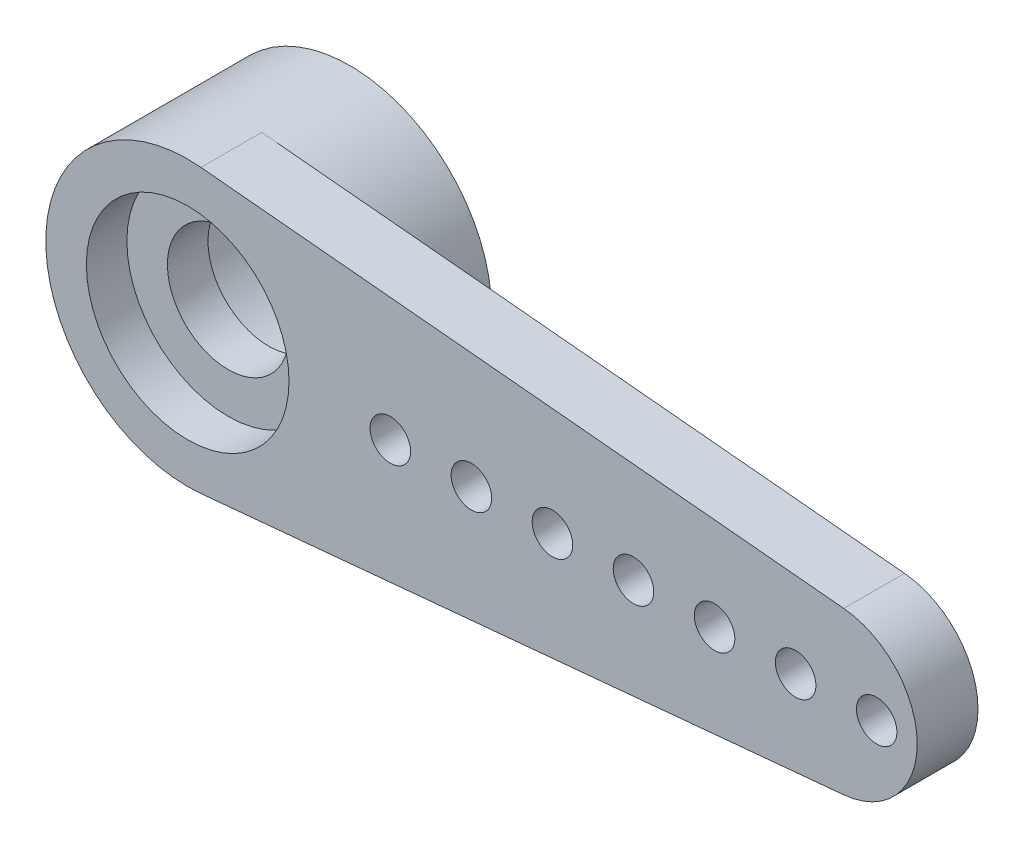
SolidWorks part; units mm, degrees
ref_plane "前视基准面" through (0, 0, 0) normal (0, 0, 1) x (1, 0, 0)
ref_plane "上视基准面" through (0, 0, 0) normal (0, 1, 0) x (1, 0, 0)
ref_plane "右视基准面" through (0, 0, 0) normal (1, 0, 0) x (0, 0, -1)
sketch "草图1" plane through (0, 0, 0) normal (0, 0, 1) x (1, 0, 0)
  circle A0 centre (0, 0) radius 3.5
  dimension "D1" = 7
extrude "凸台-拉伸1" add sketch "草图1" along normal blind 4
sketch "草图2" plane through (0, 0, 4) normal (0, 0, 1) x (1, 0, 0)
  line L0 (0, 0) -> (16, 0) construction
  line L1 (0.3281, 3.4846) -> (16.1875, 1.9912)
  line L2 (16.1875, -1.9912) -> (0.3281, -3.4846)
  arc A0 (16.1875, -1.9912) -> (16.1875, 1.9912) centre (16, 0) ccw
  circle A1 centre (0, 0) radius 3.5 construction
  arc A2 (0.3281, -3.4846) -> (0.3281, 3.4846) centre (0, 0) ccw
  dimension "D2" = 4
  dimension "D1" = 16
extrude "凸台-拉伸2" add sketch "草图2" against normal blind 1.5
sketch "草图3" plane through (0, 0, 2.5) normal (0, 0, -1) x (-1, 0, 0)
  line L0 (-16, 0) -> (-14, 0) construction
  line L1 (-18.4851, 0) -> (5.3672, 0) construction
  circle A0 centre (-7, 0) radius 0.5
  circle A1 centre (-9, 0) radius 0.5
  circle A2 centre (-11, 0) radius 0.5
  circle A3 centre (-13, 0) radius 0.5
  circle A4 centre (-15, 0) radius 0.5
  circle A5 centre (-5, 0) radius 0.5
  circle A10 centre (-17, 0) radius 0.5
  dimension "D1" = 7
  dimension "D2" = 1
  dimension "D5" = 5
extrude "切除-拉伸1" cut sketch "草图3" against normal blind 1.5
sketch "草图4" plane through (0, 0, 0) normal (0, 0, -1) x (-1, 0, 0)
  circle A0 centre (0, 0) radius 1.5
  dimension "D1" = 3
extrude "切除-拉伸2" cut sketch "草图4" against normal blind 55
sketch "草图5" plane through (0, 0, 0) normal (0, 0, -1) x (-1, 0, 0)
  circle A0 centre (0, 0) radius 2.5
  dimension "D1" = 5
extrude "切除-拉伸3" cut sketch "草图5" against normal blind 2
sketch "草图6" plane through (0, 0, 4) normal (0, 0, 1) x (1, 0, 0)
  circle A0 centre (0, 0) radius 2.5
  dimension "D1" = 5
extrude "切除-拉伸4" cut sketch "草图6" against normal blind 1
mirror "镜向1" [suppressed] about plane through (0, 0, 0) normal (1, 0, 0)
